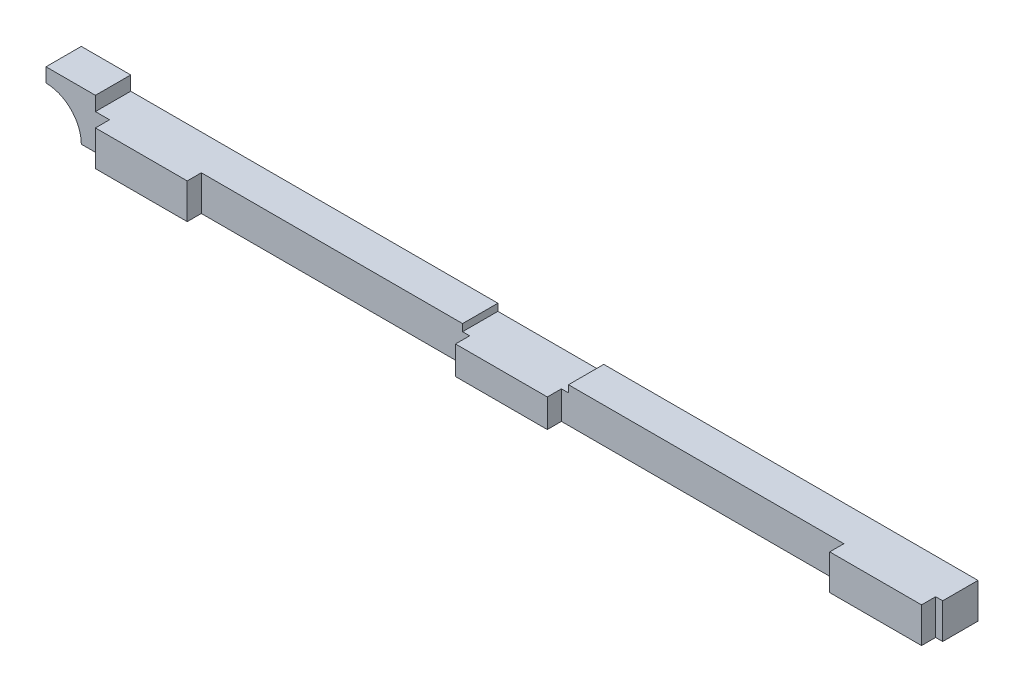
SolidWorks part; units mm, degrees
ref_plane "Plan de face" through (0, 0, 0) normal (0, 0, 1) x (1, 0, 0)
ref_plane "Plan de dessus" through (0, 0, 0) normal (0, 1, 0) x (1, 0, 0)
ref_plane "Plan de droite" through (0, 0, 0) normal (1, 0, 0) x (0, 0, -1)
sketch "Base pièce" plane through (0, 0, 0) normal (0, 0, 1) x (1, 0, 0)
  line L0 (0, 0) -> (15, 0)
  line L1 (15, 0) -> (15, 1)
  line L2 (15, 1) -> (68, 1)
  line L3 (68, 1) -> (68, -4)
  line L4 (68, -4) -> (-54, -4)
  line L5 (0, 0) -> (0, 1)
  line L6 (0, 1) -> (-52, 1)
  line L7 (-52, 1) -> (-52, 3)
  line L8 (-52, 3) -> (-59, 3)
  line L9 (-59, 3) -> (-59, 1)
  arc A0 (-54, -4) -> (-59, 1) centre (-59, -4) ccw
  dimension "D8" = 5
  dimension "D1" = 1
  dimension "D2" = 1
  dimension "D3" = 15
  dimension "D4" = 5
  dimension "D5" = 2
  dimension "D6" = 2
  dimension "D7" = 7
  dimension "D9" = 53
  dimension "D10" = 52
extrude "Boss.-Extru.1" add sketch "Base pièce" along normal blind 5 contours L4 A0 L9 L8 L7 L6 L5 L0 L1 L2 L3
sketch "Trou 1" plane through (0, 3, 0) normal (0, 1, 0) x (1, 0, 0)
  line L0 (-59, -5) -> (-59, 0) construction
  line L1 (-52, -5) -> (-59, -5) construction
  circle A0 centre (-57.5, -2.5) radius 0.5
  dimension "D2" = 1
  dimension "D1" = 1.5
  dimension "D3" = 2.5
sketch "Autres trous" plane through (0, 1, 0) normal (0, 1, 0) x (1, 0, 0)
  line L0 (-59, -5) -> (-59, 0) construction
  line L1 (0, -5) -> (-52, -5) construction
  line L2 (15, -5) -> (68, -5) construction
  circle A0 centre (-35.5, -2.5) radius 0.5
  circle A1 centre (-17, -2.5) radius 0.5
  circle A2 centre (-4.5, -2.5) radius 0.5
  circle A3 centre (23.5, -2.5) radius 0.5
  circle A4 centre (37, -2.5) radius 0.5
  point P16 (-59, -2.5)
  dimension "D1" = 1
  dimension "D4" = 1
  dimension "D7" = 1
  dimension "D10" = 1
  dimension "D11" = 1
  dimension "D2" = 23.5
  dimension "D3" = 2.5
  dimension "D5" = 2.5
  dimension "D6" = 42
  dimension "D8" = 2.5
  dimension "D9" = 54.5
  dimension "D12" = 2.5
  dimension "D13" = 2.5
  dimension "D14" = 82.5
  dimension "D15" = 96
sketch "Esquisse3" plane through (0, 0, 5) normal (0, 0, 1) x (1, 0, 0)
  line L0 (0, 1) -> (-52, 1) construction
  line L1 (-50, 1) -> (-37, 1)
  line L2 (-50, 1) -> (-50, -4)
  line L3 (-50, -4) -> (-37, -4)
  line L4 (-37, 1) -> (-37, -4)
  line L5 (68, -4) -> (-54, -4) construction
  line L6 (0, 0) -> (15, 0) construction
  line L7 (1, 0) -> (14, 0)
  line L8 (1, 0) -> (1, -4)
  line L9 (1, -4) -> (14, -4)
  line L10 (14, 0) -> (14, -4)
  line L11 (15, 1) -> (68, 1) construction
  line L12 (54, 1) -> (67, 1)
  line L13 (54, 1) -> (54, -4)
  line L14 (54, -4) -> (67, -4)
  line L15 (67, 1) -> (67, -4)
  line L16 (-52, 1) -> (-52, 3) construction
  line L17 (0, 0) -> (0, 1) construction
  line L18 (68, 1) -> (68, -4) construction
  dimension "D1" = 13
  dimension "D2" = 13
  dimension "D3" = 13
  dimension "D4" = 2
  dimension "D5" = 1
  dimension "D6" = 1
extrude "Boss.-Extru.2" add sketch "Esquisse3" along normal blind 2
